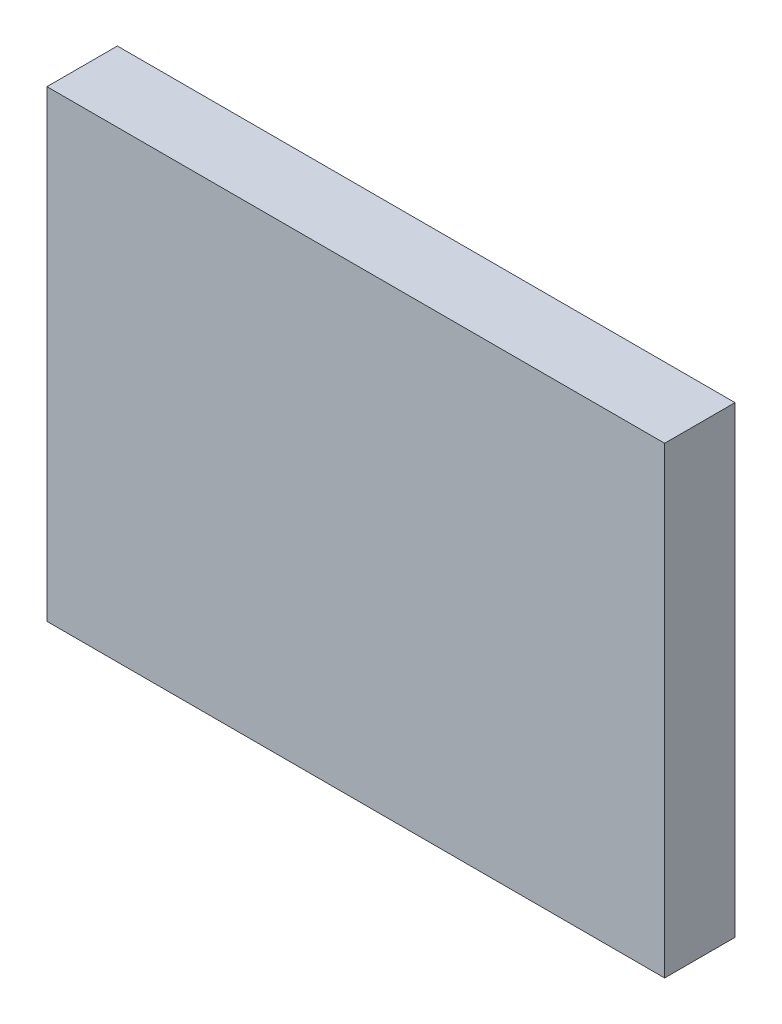
SolidWorks part; units mm, degrees
ref_plane "Front Plane" through (0, 0, 0) normal (0, 0, 1) x (1, 0, 0)
ref_plane "Top Plane" through (0, 0, 0) normal (0, 1, 0) x (1, 0, 0)
ref_plane "Right Plane" through (0, 0, 0) normal (1, 0, 0) x (0, 0, -1)
sketch "Sketch1" plane through (0, 0, 0) normal (0, 1, 0) x (1, 0, 0)
  line L1 (0, 0) -> (4000, 0)
  line L2 (0, 0) -> (0, 455.9326)
  line L3 (0, 455.9326) -> (4000, 455.9326)
  line L4 (4000, 0) -> (4000, 455.9326)
  dimension "D1" = 4000
extrude "Boss-Extrude1" add sketch "Sketch1" along normal blind 2999
